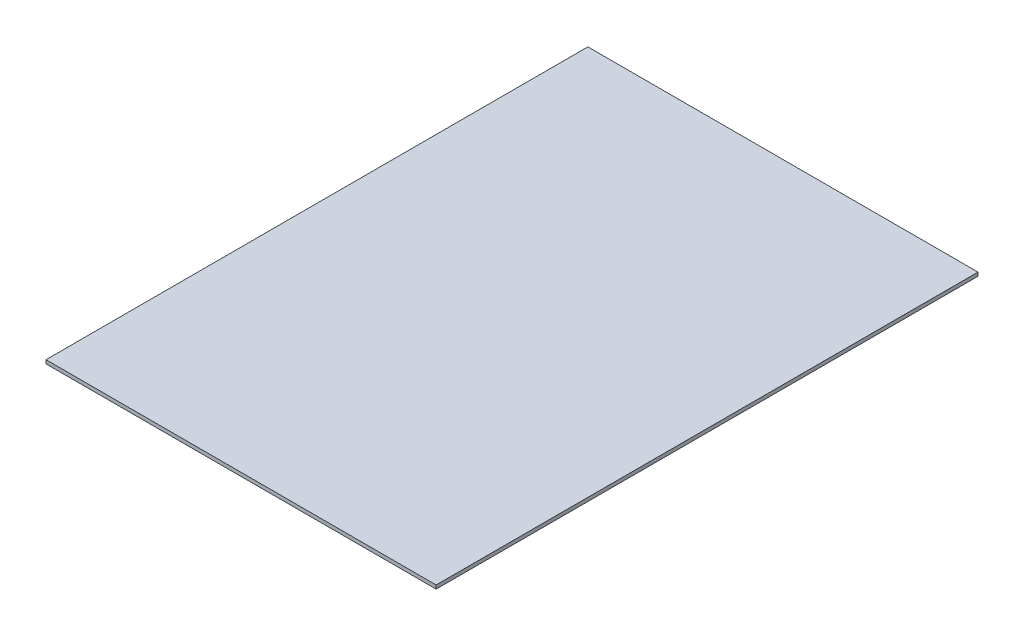
SolidWorks part; units mm, degrees
ref_plane "Front Plane" through (0, 0, 0) normal (0, 0, 1) x (1, 0, 0)
ref_plane "Top Plane" through (0, 0, 0) normal (0, 1, 0) x (1, 0, 0)
ref_plane "Right Plane" through (0, 0, 0) normal (1, 0, 0) x (0, 0, -1)
sketch "Sketch1" plane through (0, 0, 0) normal (0, 1, 0) x (1, 0, 0)
  line L1 (0, 0) -> (-540, 0)
  line L2 (0, 0) -> (0, -750)
  line L3 (0, -750) -> (-540, -750)
  line L4 (-540, 0) -> (-540, -750)
  dimension "D1" = 540
  dimension "D2" = 750
extrude "Boss-Extrude1" add sketch "Sketch1" along normal blind 5
